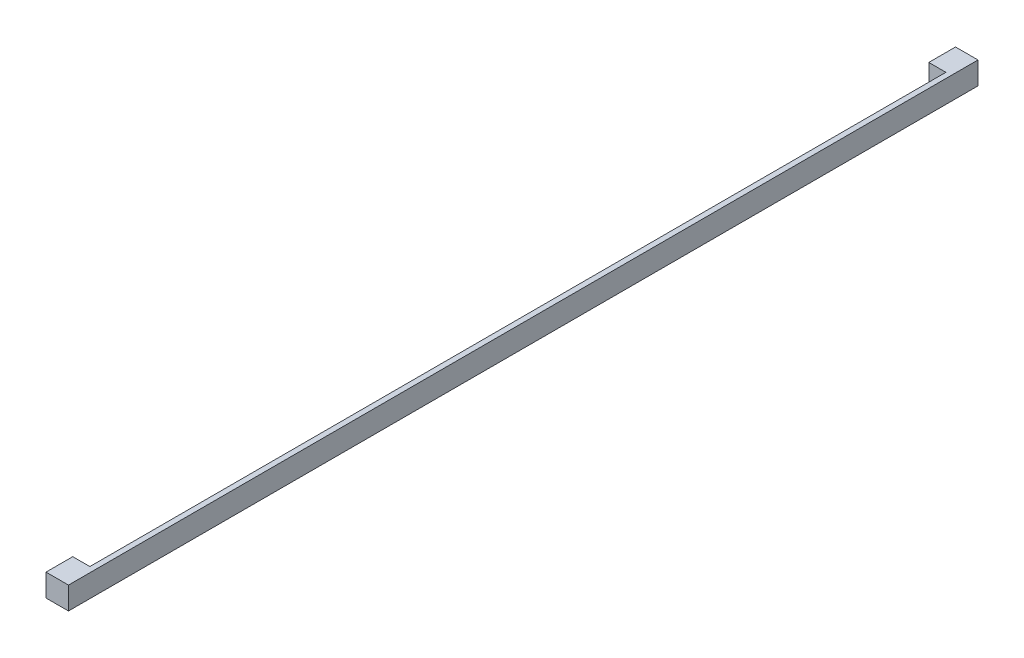
SolidWorks part; units mm, degrees
material "6061 Сплав"
ref_plane "Спереди" through (0, 0, 0) normal (0, 0, 1) x (1, 0, 0)
ref_plane "Сверху" through (0, 0, 0) normal (0, 1, 0) x (1, 0, 0)
ref_plane "Справа" through (0, 0, 0) normal (1, 0, 0) x (0, 0, -1)
sketch "Эскиз1" plane through (0, 0, 0) normal (0, 0, 1) x (1, 0, 0)
  line L1 (-4.2, -4.2) -> (4.2, -4.2)
  line L2 (-4.2, -4.2) -> (-4.2, 4.2)
  line L3 (-4.2, 4.2) -> (4.2, 4.2)
  line L4 (4.2, -4.2) -> (4.2, 4.2)
  line L5 (-4.2, -4.2) -> (4.2, 4.2) construction
  line L6 (-4.2, 4.2) -> (4.2, -4.2) construction
  point P0 (0, 0)
  dimension "D1" = 8.4
  dimension "D2" = 8.4
extrude "Бобышка-Вытянуть1" add sketch "Эскиз1" along normal blind 340
sketch "Эскиз3" plane through (0, 4.2, 0) normal (0, 1, 0) x (1, 0, 0)
  line L0 (4.2, -340) -> (-4.2, -340) construction
  line L1 (-14.8601, -10) -> (2.2, -10)
  line L2 (-14.8601, -10) -> (-14.8601, -330)
  line L3 (-14.8601, -330) -> (2.2, -330)
  line L4 (2.2, -10) -> (2.2, -330)
  line L5 (4.2, 0) -> (-4.2, 0) construction
  line L6 (4.2, -340) -> (4.2, 0) construction
  dimension "D1" = 10
  dimension "D2" = 10
  dimension "D3" = 2
extrude "Вырез-Вытянуть1" cut sketch "Эскиз3" against normal blind 6.4
